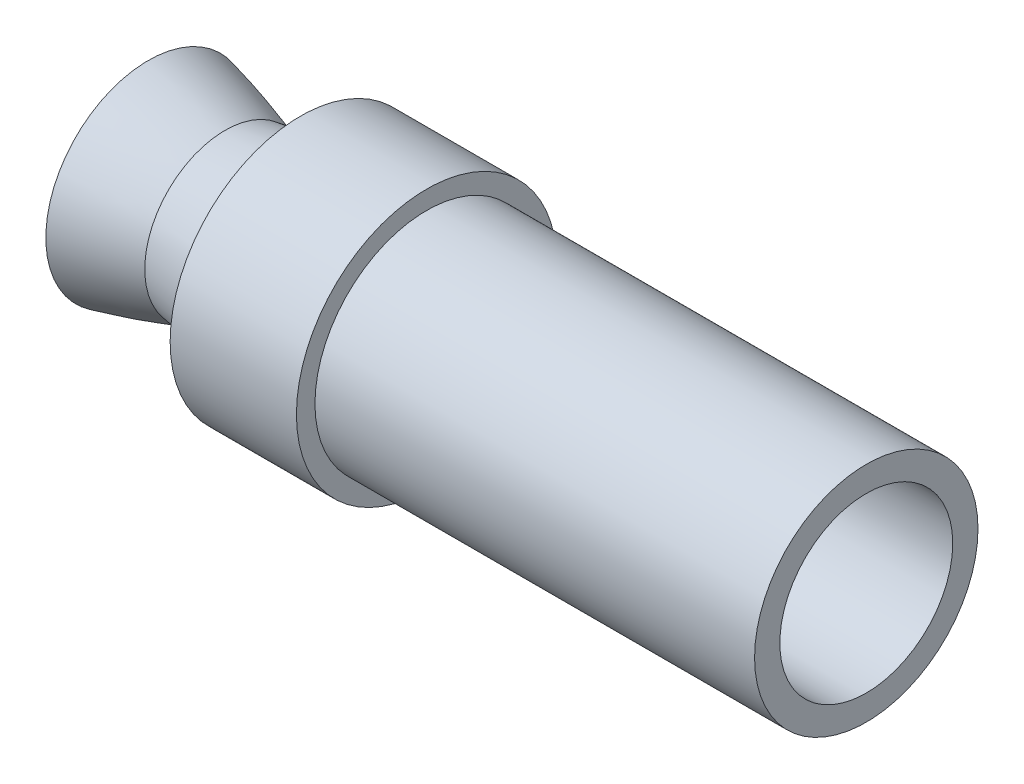
SolidWorks part; units mm, degrees
material "Polyester Resin"
ref_plane "Front Plane" through (0, 0, 0) normal (0, 0, 1) x (1, 0, 0)
ref_plane "Top Plane" through (0, 0, 0) normal (0, 1, 0) x (1, 0, 0)
ref_plane "Right Plane" through (0, 0, 0) normal (1, 0, 0) x (0, 0, -1)
sketch "Sketch1" plane through (0, 0, 0) normal (0, 0, 1) x (1, 0, 0)
  line L0 (189.133, 27.386) -> (28.9492, 27.386)
  line L1 (21.8782, 24.4571) -> (13.5417, 16.1206)
  line L3 (0, 0) -> (-234.9488, 0) construction
  line L5 (16.2213, 30.1139) -> (-13.9816, 25.4377)
  line L8 (189.133, 35.386) -> (28.9492, 35.386)
  line L12 (16.2213, 30.1139) -> (7.8848, 21.7775)
  line L13 (189.133, 27.386) -> (189.133, 35.386)
  line L14 (-40.127, 24.64) -> (-38.315, 32.4321)
  arc A0 (28.9492, 27.386) -> (21.8782, 24.4571) centre (28.9492, 17.386) ccw
  arc A4 (28.9492, 35.386) -> (16.2213, 30.1139) centre (28.9492, 17.386) ccw
  arc A7 (2.3482, 19.2268) -> (2.3482, 19.2268) centre (2.3482, 19.2268) cw
  arc A8 (7.8848, 21.7775) -> (2.3482, 19.2268) centre (1.6623, 28) cw construction
  arc A9 (2.3482, 19.2268) -> (7.8848, 21.7775) centre (1.6623, 28) ccw
  arc A10 (0.1069, 11.2722) -> (0, 11.5361) centre (3.1693, 12.6659) cw construction
  arc A11 (13.5417, 16.1206) -> (0.1069, 11.2722) centre (1.6623, 28) cw construction
  arc A12 (13.5417, 16.1206) -> (1.6623, 11.2) centre (1.6623, 28) cw
  arc A13 (1.6623, 11.2) -> (0, 11.5361) centre (1.6623, 15.4784) cw
  spline S0 degree 2 poles (0, 11.5361) (-19.9483, 19.9476) (-40.127, 24.64) knots 0 0 0 1 1 1 construction
  spline S1 degree 1 poles (2.3482, 19.2268) (-38.315, 32.4321) knots 0 0 1 1 construction
  spline S2 degree 2 poles (0, 11.5361) (-19.9483, 19.9476) (-40.127, 24.64) knots 0 0 0 1 1 1
  spline S3 degree 2 poles (2.3482, 19.2268) (0.3135, 20.0775) (-5.8003, 22.5182) (-13.9784, 25.475) (-28.1602, 30.0701) (-38.315, 32.4321) knots 0.018494 0.018494 0.018494 0.117488 0.315475 0.513463 1 1 1
  dimension "D1" = 10
  dimension "D4" = 16.8
  dimension "D5" = 4.2784
  dimension "D14" = 27.386
  dimension "D16" = 167.2548
  dimension "D2" = 11.2
  dimension "D6" = 45
  dimension "D7" = 24.64
  dimension "D3" = 8
revolve "Revolve1" add sketch "Sketch1" angle 360 about L3
ref_plane "Plane1" through (0, 0, 40) normal (0, 0, 1) x (1, 0, 0)
sketch "Sketch2" plane through (0, 0, 40) normal (0, 0, 1) x (1, 0, 0)
  line L0 (-13.9816, 25.4377) -> (-13.9816, -25.4377) construction
  line L2 (16.2213, -30.1139) -> (16.2213, 30.1139) construction
  line L3 (-13.9816, 25.4377) -> (-13.9816, -25.4377) construction
  line L4 (-13.9816, 0) -> (16.2213, 0) construction
  line L6 (1.6623, 11.2) -> (1.6623, -11.2) construction
  circle A0 centre (1.6623, 0) radius 2.5
  dimension "D2" = 5
sketch "Sketch3" plane through (0, 0, 0) normal (0, 0, 1) x (1, 0, 0)
  line L0 (16.2213, 30.1139) -> (7.8848, 21.7775) construction
  line L1 (16.2213, 30.1139) -> (7.8848, 21.7775)
  line L2 (9.8782, 23.7708) -> (9.8782, 41.25)
  line L3 (9.8782, 41.25) -> (49.8782, 41.25)
  line L4 (49.8782, 41.25) -> (49.8782, 35.386)
  line L5 (189.133, 35.386) -> (28.9492, 35.386) construction
  line L6 (200000, 0) -> (-200234.9488, 0) construction
  line L7 (28.9492, 35.386) -> (28.9492, -35.386) construction
  line L8 (28.9492, 35.386) -> (28.9492, -35.386)
  line L9 (189.133, 35.386) -> (28.9492, 35.386)
  line L10 (21.8782, 24.4571) -> (21.8782, -24.4571) construction
  line L11 (21.8782, 24.4571) -> (21.8782, -24.4571)
  line L12 (16.2213, 30.1139) -> (-13.9816, 25.4377) construction
  line L13 (16.2213, 30.1139) -> (-13.9816, 25.4377)
  arc A0 (2.3482, 19.2268) -> (7.8848, 21.7775) centre (1.6623, 28) ccw construction
  arc A1 (2.3482, 19.2268) -> (7.8848, 21.7775) centre (1.6623, 28) ccw
  arc A2 (28.9492, 35.386) -> (16.2213, 30.1139) centre (28.9492, 17.386) ccw construction
  arc A3 (28.9492, 35.386) -> (16.2213, 30.1139) centre (28.9492, 17.386) ccw
  spline S0 degree 2 poles (824.9181, -2826.7846) (519.5707, -187.2178) (-5.8003, 22.5182) (-13.9784, 25.475) (-595.1339, 213.7792) (-1417.6005, -2562.2608) knots -25.204644 -25.204644 -25.204644 0.117488 0.315475 0.513463 28.366592 28.366592 28.366592 only from (2.3482, 19.2268) to (-38.315, 32.4321) construction
  spline S1 degree 2 poles (2.3482, 19.2268) (0.3135, 20.0775) (-5.8003, 22.5182) (-13.9784, 25.475) (-28.1602, 30.0701) (-38.315, 32.4321) knots 0.018494 0.018494 0.018494 0.117488 0.315475 0.513463 1 1 1
  dimension "D1" = 40
  dimension "D2" = 41.25
  dimension "D3" = 12
revolve "Revolve2" add sketch "Sketch3" angle 360 about L3
equation "\"theta_t\"= 36.9009 - ( 426.271 / ( \"Aet\" + 7.00037 ) ) + ( 10026.8 / ( \"Aet\" + 7.00037 ) ^ 2 ) - ( 175410 / ( \"Aet\" + 7.00037 ) ^ 3 ) + ( ( 1.6742 * ( 10 ^ 6 ) ) / ( \"Aet\" + 7.00037 ) ^ 4 ) - ( ( 6.7643 * ( 10 ^ 6 ) ) / ( \"Aet\" + 7.00037 ) ^ 5 )"
equation "\"rt\"= 11.2"
equation "\"re\"= sqr ( \"rt\" ^ 2 * \"Aet\" )"
equation "\"Aet\"= 4.84"
equation "\"L\"= 0.8 * ( ( \"re\" / tan ( 15 ) ) - ( \"rt\" / tan ( 15 ) ) )"
equation "\"lc\"= ( \"l*\" / \"cr\" )"
equation "\"b\"= tan ( \"theta_t\" )"
equation "\"a\"= ( \"re\" - \"b\" * \"L\" - \"c\" ) / \"L\" ^ 2"
equation "\"c\"= \"rt\" * ( 1.382 - 0.382 * cos ( \"theta_t\" ) )"
equation "\"cr\"= 5.9789"
equation "\"rc\"= sqr ( \"cr\" * ( \"rt\" ^ 2 ) )"
equation "\"D14@Sketch1\"=\"rc\""
equation "\"l*\"= 1000"
equation "\"D16@Sketch1\"=\"lc\""
equation "\"th\"= 8"
equation "\"theta_cr\"= 45deg"
equation "\"theta_e\"= 5.48 + ( 134.316 / ( \"Aet\" + 1.49269 ) ) - ( 1742.02 / ( \"Aet\" + 1.49269 ) ^ 2 ) + ( 13091 / ( \"Aet\" + 1.49269 ) ^ 3 ) - ( 41929.9 / ( \"Aet\" + 1.49269 ) ^ 4 ) + ( 44445.1 / ( \"Aet\" + 1.49269 ) ^ 5 )"
equation "\"Nx\"= 0"
equation "\"Ny\"= \"c\""
equation "\"Qx\"= ( \"re\" - ( tan ( \"theta_e\" ) * \"L\" ) - \"c\" ) / ( tan ( \"theta_t\" ) - tan ( \"theta_e\" ) )"
equation "\"Qy\"= tan ( \"theta_t\" ) * \"Qx\" + \"c\""
equation "\"Ex\"= \"L\""
equation "\"Ey\"= \"re\""
equation "\"D3@Sketch1\"=\"th\""
equation "\"D2@Sketch1\"=\"rt\""
equation "\"D4@Sketch1\"=\"rt\"*1.5"
equation "\"D5@Sketch1\"=\"rt\"*0.382"
equation "\"D6@Sketch1\"=\"theta_cr\""
equation "\"D7@Sketch1\"=\"re\""
equation "\"D2@Sketch3\"=(88.9)/2 -3.2"
